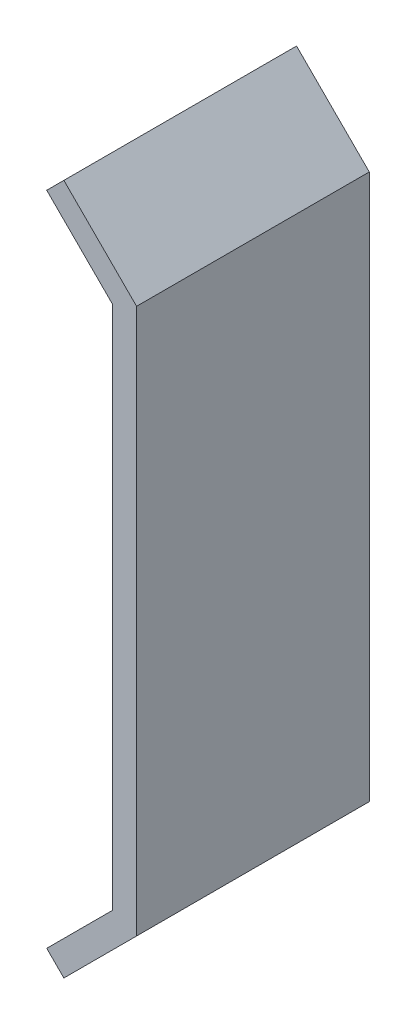
SolidWorks part; units mm, degrees
ref_plane "前视基准面" through (0, 0, 0) normal (0, 0, 1) x (1, 0, 0)
ref_plane "上视基准面" through (0, 0, 0) normal (0, 1, 0) x (1, 0, 0)
ref_plane "右视基准面" through (0, 0, 0) normal (1, 0, 0) x (0, 0, -1)
sketch "草图1" plane through (0, 0, 0) normal (0, 0, 1) x (1, 0, 0)
  line L0 (0, 0) -> (-3, 3)
  line L1 (-3, 3) -> (-3, 25.5)
  line L2 (-3, 25.5) -> (0, 28.5)
  line L3 (0, 28.5) -> (3, 25.5)
  line L4 (3, 25.5) -> (3, 3)
  line L5 (3, 3) -> (0, 0)
  dimension "D1" = 22.5
  dimension "D2" = 28.5
  dimension "D3" = 135
extrude "凸台-拉伸1" add sketch "草图1" along normal blind 1.6
sketch "草图2" plane through (0, 0, 1.6) normal (0, 0, 1) x (1, 0, 0)
  line L0 (0, 1.4142) -> (2, 3.4142)
  line L1 (2, 3.4142) -> (2, 25.0858)
  line L2 (2, 25.0858) -> (0, 27.0858)
  line L3 (0, 27.0858) -> (-2, 25.0858)
  line L4 (-2, 25.0858) -> (-2, 3.4142)
  line L5 (-2, 3.4142) -> (0, 1.4142)
  line L6 (0, 0) -> (3, 3)
  line L7 (3, 3) -> (3, 25.5)
  line L8 (3, 25.5) -> (0, 28.5)
  line L9 (0, 28.5) -> (-3, 25.5)
  line L10 (-3, 25.5) -> (-3, 3)
  line L11 (-3, 3) -> (0, 0)
  line L12 (0, 0) -> (3, 3)
  line L13 (3, 3) -> (3, 25.5)
  line L14 (3, 25.5) -> (0, 28.5)
  line L15 (0, 28.5) -> (-3, 25.5)
  line L16 (-3, 25.5) -> (-3, 3)
  line L17 (-3, 3) -> (0, 0)
  dimension "D1" = 0
  dimension "D2" = 1
extrude "凸台-拉伸2" add sketch "草图2" along normal blind 8
sketch "草图3" plane through (0, 0, 9.6) normal (0, 0, 1) x (1, 0, 0)
  line L0 (0, 27.0858) -> (-0.7071, 27.7929)
  line L1 (0, 28.5) -> (-3, 25.5) construction
  line L2 (-0.7071, 27.7929) -> (-3, 25.5)
  line L3 (-3, 25.5) -> (-3, 3)
  line L4 (-3, 3) -> (-0.7071, 0.7071)
  line L5 (-3, 3) -> (0, 0) construction
  line L6 (-0.7071, 0.7071) -> (0, 1.4142)
  line L7 (0, 1.4142) -> (-2, 3.4142)
  line L8 (-2, 3.4142) -> (-2, 25.0858)
  line L9 (-2, 25.0858) -> (0, 27.0858)
  line L10 (0, 1.4142) -> (2, 3.4142) construction
extrude "切除-拉伸1" cut sketch "草图3" against normal blind 8
equation "\"1。6\"=3"
